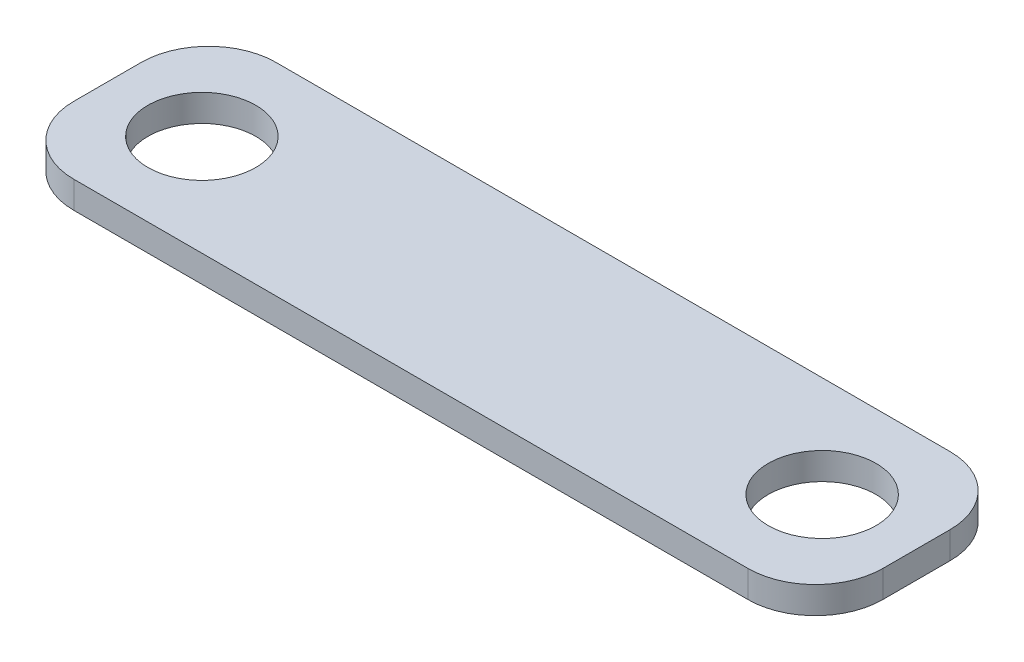
SolidWorks part; units mm, degrees
ref_plane "Front Plane" through (0, 0, 0) normal (0, 0, 1) x (1, 0, 0)
ref_plane "Top Plane" through (0, 0, 0) normal (0, 1, 0) x (1, 0, 0)
ref_plane "Right Plane" through (0, 0, 0) normal (1, 0, 0) x (0, 0, -1)
sketch "Sketch1" plane through (0, 0, 0) normal (0, 1, 0) x (1, 0, 0)
  line L1 (0, 1.7031) -> (60, 1.7031)
  line L2 (0, 1.7031) -> (0, 16.7031)
  line L3 (0, 16.7031) -> (60, 16.7031)
  line L4 (60, 1.7031) -> (60, 16.7031)
  dimension "D1" = 60
  dimension "D2" = 15
extrude "Boss-Extrude1" add sketch "Sketch1" along normal blind 2
sketch "Sketch2" plane through (0, 2, 0) normal (0, 1, 0) x (1, 0, 0)
  line L0 (0, 16.7031) -> (0, 1.7031) construction
  line L1 (0, 1.7031) -> (60, 1.7031) construction
  line L2 (60, 16.7031) -> (0, 16.7031) construction
  line L3 (30, 16.7031) -> (30, 1.7031)
  circle A0 centre (7, 9.2031) radius 4
  circle A1 centre (53, 9.2031) radius 4
  dimension "D1" = 8
  dimension "D2" = 7
  dimension "D3" = 7.5
extrude "Cut-Extrude1" cut sketch "Sketch2" against normal blind 2 contours A0 | A1
fillet "Fillet2" radius 5 4 edges at (60, 1, -16.7031) (60, 1, -1.7031) (0, 1, -1.7031) (0, 1, -16.7031)
